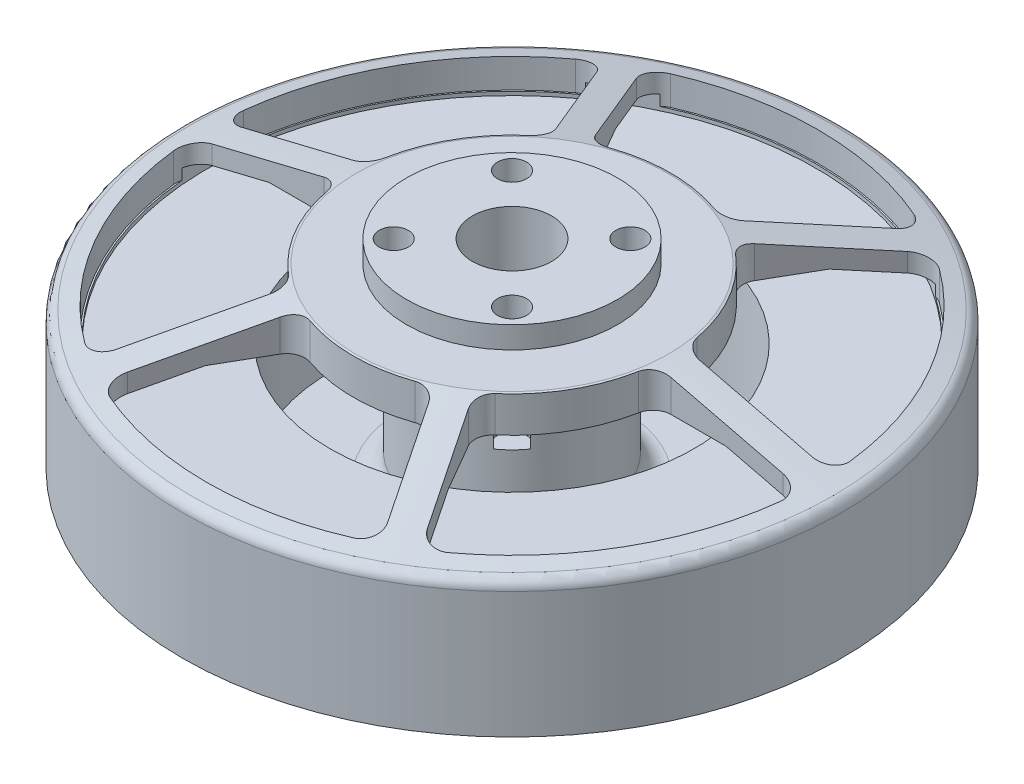
SolidWorks part; units mm, degrees
ref_plane "前视基准面" through (0, 0, 0) normal (0, 0, 1) x (1, 0, 0)
ref_plane "上视基准面" through (0, 0, 0) normal (0, 1, 0) x (1, 0, 0)
ref_plane "右视基准面" through (0, 0, 0) normal (1, 0, 0) x (0, 0, -1)
sketch "草图2" plane through (0, 0, 0) normal (0, 0, 1) x (1, 0, 0)
  line L0 (0, 0) -> (-29.5, 0)
  line L1 (-29.5, 0) -> (-29.5, 1)
  line L2 (-41.8, 6.1) -> (-45.3, 6.1)
  line L3 (-45.3, 6.1) -> (-45.3, 22.2)
  line L4 (-45.3, 22.2) -> (0, 22.2) construction
  line L5 (0, 22.2) -> (0, 0)
  line L6 (-45.3, 22.2) -> (-45.3, 23.4216)
  line L7 (-44.1551, 24.879) -> (-21.4963, 30.4)
  line L8 (-21.4963, 30.4) -> (-14.5, 30.4)
  line L9 (0, 30.4) -> (0, 22.2)
  line L10 (0, 30.4) -> (0, 33.4)
  line L11 (0, 33.4) -> (-14.5, 33.4)
  line L12 (-14.5, 33.4) -> (-14.5, 30.4)
  line L13 (-29.5, 1) -> (-26.7, 1)
  line L14 (-26.7, 1) -> (-26.7, 7.1)
  line L15 (-25, 5) -> (-25, 20.8797)
  line L16 (-25, 20.8797) -> (-41.8, 20.8797)
  line L17 (-41.8, 20.8797) -> (-41.8, 22.8797)
  line L18 (-41.8, 22.8797) -> (-31.4563, 25.4)
  line L19 (-31.4563, 25.4) -> (-12.5, 25.4)
  line L20 (-12.5, 25.4) -> (-12.5, 8)
  line L21 (-15.5, 5) -> (-25, 5)
  line L22 (-41.8, 6.1) -> (-41.8, 7.1)
  line L23 (-41.8, 7.1) -> (-26.7, 7.1)
  arc A0 (-45.3, 23.4216) -> (-44.1551, 24.879) centre (-43.8, 23.4216) cw
  arc A1 (-12.5, 8) -> (-15.5, 5) centre (-15.5, 8) cw
  point P13 (-45.3, 24.6)
  point P30 (-26.7, 7.8344)
  dimension "D8" = 1.5
  dimension "D18" = 3
  dimension "D2" = 29.5
  dimension "D3" = 16.1
  dimension "D4" = 45.3
  dimension "D5" = 30.4
  dimension "D6" = 2.4
  dimension "D7" = 21.4963
  dimension "D9" = 14.5
  dimension "D10" = 3
  dimension "D11" = 1
  dimension "D12" = 2.8
  dimension "D13" = 6.1
  dimension "D14" = 2.5
  dimension "D15" = 3.5
  dimension "D16" = 25
  dimension "D17" = 12.5
  dimension "D19" = 5
  dimension "D20" = 2
  dimension "D21" = 5
  dimension "D22" = 1
revolve "旋转1" add sketch "草图2" angle 360 about L5
sketch "草图7" plane through (0, 30.4, 0) normal (0, 1, 0) x (1, 0, 0)
  line L0 (-21, 36.3731) -> (0, 0) construction
  line L1 (0, 0) -> (21, 36.3731) construction
  line L2 (-17.8894, 34.9853) -> (-10.2078, 21.6804)
  line L3 (17.8894, 34.9853) -> (10.2078, 21.6804)
  line L4 (0, 0) -> (0, 54.7319) construction
  line L5 (39.2428, 2) -> (23.8797, 2)
  line L6 (21.3535, 32.9853) -> (13.6719, 19.6804)
  line L7 (21.3535, -32.9853) -> (13.6719, -19.6804)
  line L8 (39.2428, -2) -> (23.8797, -2)
  line L9 (-17.8894, -34.9853) -> (-10.2078, -21.6804)
  line L10 (17.8894, -34.9853) -> (10.2078, -21.6804)
  line L11 (-39.2428, -2) -> (-23.8797, -2)
  line L12 (-21.3535, -32.9853) -> (-13.6719, -19.6804)
  line L13 (-21.3535, 32.9853) -> (-13.6719, 19.6804)
  line L14 (-39.2428, 2) -> (-23.8797, 2)
  arc A0 (-21, 36.3731) -> (21, 36.3731) centre (0, 0) cw construction
  arc A1 (-7.2153, 20.5713) -> (7.2153, 20.5713) centre (0, 0) cw
  arc A2 (-16.7195, 38.5287) -> (16.7195, 38.5287) centre (0, 0) cw
  arc A3 (-10.2078, 21.6804) -> (-7.2153, 20.5713) centre (-8.0427, 22.9304) ccw
  arc A4 (7.2153, 20.5713) -> (10.2078, 21.6804) centre (8.0427, 22.9304) ccw
  arc A5 (16.7195, 38.5287) -> (17.8894, 34.9853) centre (15.7243, 36.2353) cw
  arc A6 (-17.8894, 34.9853) -> (-16.7195, 38.5287) centre (-15.7243, 36.2353) cw
  arc A7 (41.7266, 4.7848) -> (39.2428, 2) centre (39.2428, 4.5) cw
  arc A8 (21.4229, 4.037) -> (23.8797, 2) centre (23.8797, 4.5) ccw
  arc A9 (14.2076, 16.5343) -> (21.4229, 4.037) centre (0, 0) cw
  arc A10 (13.6719, 19.6804) -> (14.2076, 16.5343) centre (15.837, 18.4304) ccw
  arc A11 (21.3535, 32.9853) -> (25.007, 33.7439) centre (23.5185, 31.7353) cw
  arc A12 (25.007, 33.7439) -> (41.7266, 4.7848) centre (0, 0) cw
  arc A13 (25.007, -33.7439) -> (21.3535, -32.9853) centre (23.5185, -31.7353) cw
  arc A14 (14.2076, -16.5343) -> (13.6719, -19.6804) centre (15.837, -18.4304) ccw
  arc A15 (21.4229, -4.037) -> (14.2076, -16.5343) centre (0, 0) cw
  arc A16 (23.8797, -2) -> (21.4229, -4.037) centre (23.8797, -4.5) ccw
  arc A17 (39.2428, -2) -> (41.7266, -4.7848) centre (39.2428, -4.5) cw
  arc A18 (41.7266, -4.7848) -> (25.007, -33.7439) centre (0, 0) cw
  arc A19 (-16.7195, -38.5287) -> (-17.8894, -34.9853) centre (-15.7243, -36.2353) cw
  arc A20 (-7.2153, -20.5713) -> (-10.2078, -21.6804) centre (-8.0427, -22.9304) ccw
  arc A21 (7.2153, -20.5713) -> (-7.2153, -20.5713) centre (0, 0) cw
  arc A22 (10.2078, -21.6804) -> (7.2153, -20.5713) centre (8.0427, -22.9304) ccw
  arc A23 (17.8894, -34.9853) -> (16.7195, -38.5287) centre (15.7243, -36.2353) cw
  arc A24 (16.7195, -38.5287) -> (-16.7195, -38.5287) centre (0, 0) cw
  arc A25 (-41.7266, -4.7848) -> (-39.2428, -2) centre (-39.2428, -4.5) cw
  arc A26 (-21.4229, -4.037) -> (-23.8797, -2) centre (-23.8797, -4.5) ccw
  arc A27 (-14.2076, -16.5343) -> (-21.4229, -4.037) centre (0, 0) cw
  arc A28 (-13.6719, -19.6804) -> (-14.2076, -16.5343) centre (-15.837, -18.4304) ccw
  arc A29 (-21.3535, -32.9853) -> (-25.007, -33.7439) centre (-23.5185, -31.7353) cw
  arc A30 (-25.007, -33.7439) -> (-41.7266, -4.7848) centre (0, 0) cw
  arc A31 (-25.007, 33.7439) -> (-21.3535, 32.9853) centre (-23.5185, 31.7353) cw
  arc A32 (-14.2076, 16.5343) -> (-13.6719, 19.6804) centre (-15.837, 18.4304) ccw
  arc A33 (-21.4229, 4.037) -> (-14.2076, 16.5343) centre (0, 0) cw
  arc A34 (-23.8797, 2) -> (-21.4229, 4.037) centre (-23.8797, 4.5) ccw
  arc A35 (-39.2428, 2) -> (-41.7266, 4.7848) centre (-39.2428, 4.5) cw
  arc A36 (-41.7266, 4.7848) -> (-25.007, 33.7439) centre (0, 0) cw
  point P4 (0, 42)
  point P17 (19.2441, 37.3318)
  point P20 (-19.2441, 37.3318)
  point P82 (0, 0)
  dimension "D1" = 42
  dimension "D5" = 21.8
  dimension "D6" = 2.5
  dimension "D2" = 60
  dimension "D3" = 4
  dimension "D4" = 4
  dimension "D7" = 6
extrude "切除-拉伸4" cut sketch "草图7" against normal blind 9
sketch "草图3" plane through (0, 33.4, 0) normal (0, 1, 0) x (1, 0, 0)
  line L1 (8.1317, -8.1317) -> (-8.1317, -8.1317) construction
  line L2 (8.1317, -8.1317) -> (8.1317, 8.1317) construction
  line L3 (8.1317, 8.1317) -> (-8.1317, 8.1317) construction
  line L4 (-8.1317, -8.1317) -> (-8.1317, 8.1317) construction
  line L5 (8.1317, -8.1317) -> (-8.1317, 8.1317) construction
  line L6 (8.1317, 8.1317) -> (-8.1317, -8.1317) construction
  circle A0 centre (0, 0) radius 11.5 construction
  circle A1 centre (-8.1317, -8.1317) radius 2
  circle A2 centre (-8.1317, 8.1317) radius 2
  circle A3 centre (8.1317, 8.1317) radius 2
  circle A4 centre (8.1317, -8.1317) radius 2
  circle A5 centre (0, 0) radius 5.44
  dimension "D1" = 23
  dimension "D2" = 4
  dimension "D3" = 10.88
extrude "切除-拉伸1" cut sketch "草图3" against normal blind 16.3
sketch "草图4" plane through (0, 0, 0) normal (0, -1, 0) x (1, 0, 0)
  line L0 (0, 15) -> (0, -15) construction
  line L1 (0, 15) -> (-10.6066, 10.6066) construction
  line L2 (-10.6066, 10.6066) -> (-15, 0) construction
  line L3 (-15, 0) -> (-10.6066, -10.6066) construction
  line L4 (-10.6066, -10.6066) -> (0, -15) construction
  line L5 (0, -15) -> (10.6066, -10.6066) construction
  line L6 (10.6066, -10.6066) -> (15, 0) construction
  line L7 (15, 0) -> (10.6066, 10.6066) construction
  line L8 (10.6066, 10.6066) -> (0, 15) construction
  line L10 (11.3137, 11.3137) -> (-11.3137, 11.3137) construction
  line L11 (-11.3137, 11.3137) -> (-11.3137, -11.3137) construction
  line L12 (-11.3137, -11.3137) -> (11.3137, -11.3137) construction
  line L13 (11.3137, -11.3137) -> (11.3137, 11.3137) construction
  circle A0 centre (0, 0) radius 15 construction
  circle A1 centre (0, 15) radius 1.5
  circle A3 centre (15, 0) radius 1.5
  circle A5 centre (0, -15) radius 1.5
  circle A7 centre (-15, 0) radius 1.5
  circle A9 centre (0, 0) radius 16 construction
  circle A10 centre (-11.3137, 11.3137) radius 2
  circle A11 centre (11.3137, 11.3137) radius 2
  circle A12 centre (11.3137, -11.3137) radius 2
  circle A13 centre (-11.3137, -11.3137) radius 2
  dimension "D1" = 30
  dimension "D2" = 3
  dimension "D3" = 4
  dimension "D4" = 32
extrude "切除-拉伸2" cut sketch "草图4" against normal blind 10
sketch "草图5" plane through (0, 0, 0) normal (0, -1, 0) x (1, 0, 0)
  line L0 (-8.5, -28.2489) -> (-8.5, -39.2489)
  line L1 (-6.5, -41.2489) -> (6.5, -41.2489)
  line L2 (8.5, -39.2489) -> (8.5, -28.2489)
  line L3 (-8.5, -28.2489) -> (-1.1296, -23.2047)
  line L4 (1.1296, -23.2047) -> (8.5, -28.2489)
  circle A0 centre (0, 0) radius 29.5 construction
  arc A1 (6.5, -41.2489) -> (8.5, -39.2489) centre (6.5, -39.2489) ccw
  arc A2 (-1.1296, -23.2047) -> (1.1296, -23.2047) centre (0, -24.8552) cw
  arc A4 (-8.5, -39.2489) -> (-6.5, -41.2489) centre (-6.5, -39.2489) ccw
  point P5 (0, 0)
  point P8 (0, 0)
  point P11 (8.5, -41.2489)
  point P14 (-8.5, -41.2489)
  point P15 (0, 0)
  point P16 (0, 0)
  point P17 (0, 0)
  point P19 (0, -41.2489)
  point P22 (0, -22.4317)
  dimension "D4" = 2
  dimension "D5" = 2
  dimension "D2" = 17
  dimension "D3" = 13
  dimension "D1" = 10.3
extrude "凸台-拉伸1" add sketch "草图5" along normal blind 1.5 separate body
sketch "草图6" plane through (0, 0, 0) normal (0, -1, 0) x (1, 0, 0)
  circle A0 centre (0, 0) radius 12.25
  circle A1 centre (0, 0) radius 8
  dimension "D1" = 24.5
  dimension "D2" = 16
extrude "切除-拉伸3" cut sketch "草图6" against normal blind 4
sketch "草图8" plane through (0, 0, 0) normal (0, -1, 0) x (1, 0, 0)
  circle A0 centre (0, 0) radius 8 construction
  circle A1 centre (0, 0) radius 8
extrude "切除-拉伸5" cut sketch "草图8" against normal blind 0.3
